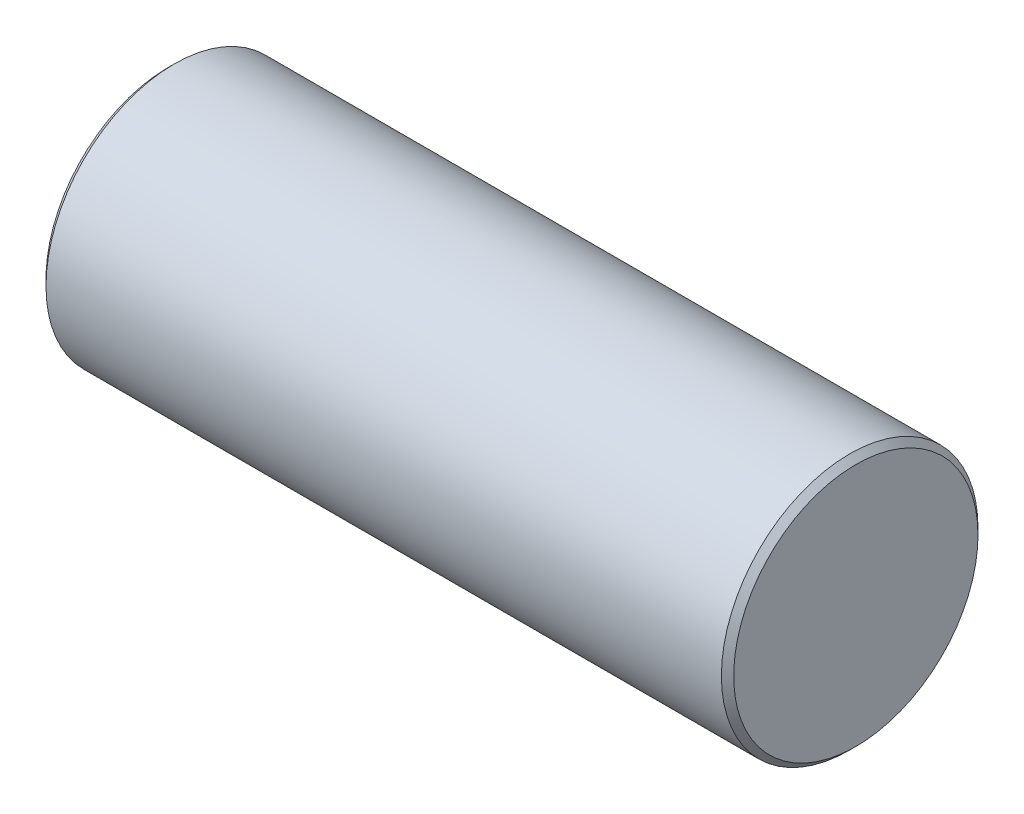
SolidWorks part; units mm, degrees
ref_plane "Front Plane" through (0, 0, 0) normal (0, 0, 1) x (1, 0, 0)
ref_plane "Top Plane" through (0, 0, 0) normal (0, 1, 0) x (1, 0, 0)
ref_plane "Right Plane" through (0, 0, 0) normal (1, 0, 0) x (0, 0, -1)
sketch "Sketch1" plane through (0, 0, 0) normal (1, 0, 0) x (0, 0, -1)
  circle A0 centre (0, 0) radius 15.875
  dimension "D1" = 31.75
extrude "Boss-Extrude1" add sketch "Sketch1" along normal mid plane 85.09
chamfer "Chamfer1" distance 0.762 angle 45 2 edges at (-42.545, 0, -15.875) (42.545, 0, -15.875)
